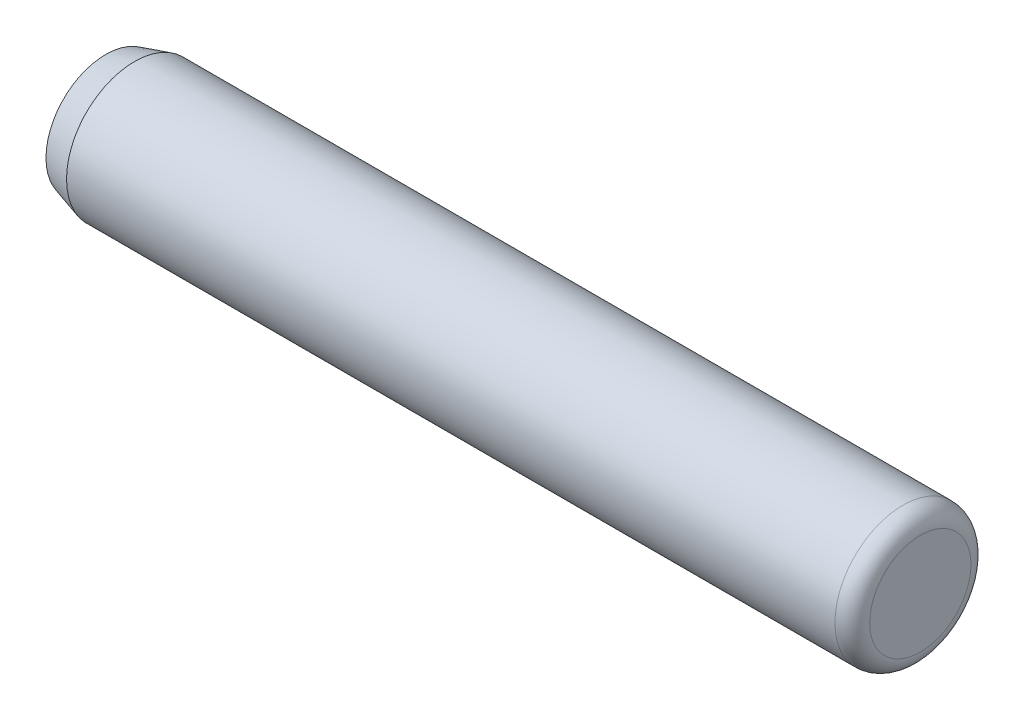
SolidWorks part; units mm, degrees
material "Plain Carbon Steel"
ref_plane "Front" through (0, 0, 0) normal (0, 0, 1) x (1, 0, 0)
ref_plane "Top" through (0, 0, 0) normal (0, 1, 0) x (1, 0, 0)
ref_plane "Right" through (0, 0, 0) normal (1, 0, 0) x (0, 0, -1)
sketch "Sketch1" plane through (0, 0, 0) normal (1, 0, 0) x (0, 0, -1)
  circle A0 centre (0, 0) radius 1.59 construction
  point P3 (0, 1.59)
  dimension "Diameter" = 3.1801
sketch "Sketch2" plane through (0, 0, 0) normal (0, 0, 1) x (1, 0, 0)
  line L0 (-9.525, 0) -> (9.525, 0) construction
  line L1 (9.525, 1.1836) -> (9.525, -0.6481) construction
  line L2 (-9.525, 1.397) -> (-9.525, -1.397) construction
  line L3 (-9.525, 1.397) -> (-9.525, 1.59) construction
  line L4 (-9.525, -1.397) -> (-9.525, -1.59) construction
  line L5 (-9.525, 1.397) -> (-8.8518, 1.59) construction
  line L6 (-8.8518, 1.59) -> (9.1186, 1.59) construction
  arc A0 (9.1186, 1.59) -> (9.525, 1.1836) centre (9.1186, 1.1836) cw construction
  point P6 (-6.3449, 0)
  point P8 (6.3449, 0)
  point P23 (8.4836, 1.59)
  dimension "Crown Radius" = 0.4064
  dimension "Length" = 19.05
  dimension "D1" = 3.1801
  dimension "D2" = 3.1801
  dimension "Point Diameter" = 2.794
  dimension "D3" = 16
  dimension "Crown Height" = 1.0414
sketch "Sketch3" plane through (0, 0, 0) normal (0, 0, 1) x (1, 0, 0)
  line L0 (9.525, 1.1836) -> (9.525, -0.6481) construction
  line L1 (-8.8518, 1.59) -> (9.1186, 1.59) construction
  line L2 (-9.525, 1.397) -> (-8.8518, 1.59) construction
  line L3 (-9.525, 1.397) -> (-9.525, -1.397) construction
  line L4 (-9.525, 0) -> (9.525, 0) construction
  line L5 (9.525, 1.1836) -> (9.525, 0)
  line L6 (-8.8518, 1.59) -> (9.1186, 1.59)
  line L7 (-9.525, 1.397) -> (-8.8518, 1.59)
  line L8 (-9.525, 1.397) -> (-9.525, 0)
  line L9 (-9.525, 0) -> (9.525, 0)
  arc A0 (9.525, 1.1836) -> (9.1186, 1.59) centre (9.1186, 1.1836) ccw construction
  arc A1 (9.525, 1.1836) -> (9.1186, 1.59) centre (9.1186, 1.1836) ccw
revolve "Revolve1" add sketch "Sketch3" angle 360 about L0
equation "\"D1@Sketch2\" = \"Diameter@Sketch1\""
equation "\"D2@Sketch2\" = \"Diameter@Sketch1\""
